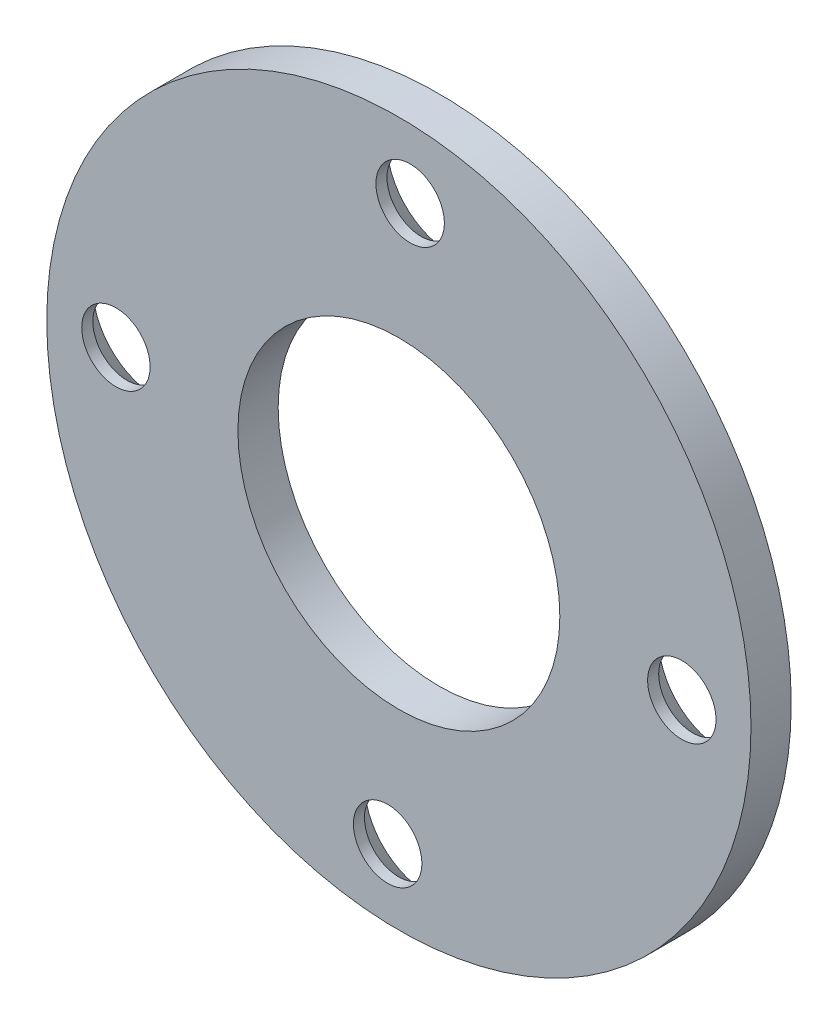
SolidWorks part; units mm, degrees
ref_plane "Front Plane" through (0, 0, 0) normal (0, 0, 1) x (1, 0, 0)
ref_plane "Top Plane" through (0, 0, 0) normal (0, 1, 0) x (1, 0, 0)
ref_plane "Right Plane" through (0, 0, 0) normal (1, 0, 0) x (0, 0, -1)
sketch "Sketch1" plane through (0, 0, 0) normal (0, 0, 1) x (1, 0, 0)
  circle A0 centre (0, 0) radius 8
  circle A1 centre (0, 0) radius 17.5
  dimension "D1" = 16
  dimension "D2" = 35
extrude "Boss-Extrude1" add sketch "Sketch1" along normal blind 2
hole_wizard "CSK for M3 Countersunk Flat Head Screw1" positions "Sketch2" profile "Sketch3" countersink size "M3" standard "ISO" end condition through all
sketch "Sketch2" plane through (0, 0, 0) normal (0, 0, -1) x (-1, 0, 0)
  point P0 (-0.5592, 14.062)
  point P3 (14.062, 0.5592)
  point P6 (0.5592, -14.062)
  point P9 (-14.062, -0.5592)
sketch "Sketch3" plane through (0.5592, 14.062, 0) normal (1, 0, 0) x (0, 1, 0)
  line L0 (0, 0) -> (0, 2)
  line L1 (0, 2) -> (1.7, 2)
  line L2 (1.7, 2) -> (1.7, 1.45)
  line L3 (1.7, 1.45) -> (3.15, 0)
  line L5 (3.15, 0) -> (0, 0)
  line L6 (-1.7, 1.45) -> (-3.15, 0) construction
  line L11 (0, -6.35) -> (0, 107.95) construction
  dimension "Thru Hole Dia." = 3.4
  dimension "Thru Hole Depth" = 2
  dimension "Near C'Sink Dia." = 6.3
  dimension "Near C'Sink Angle" = 90
